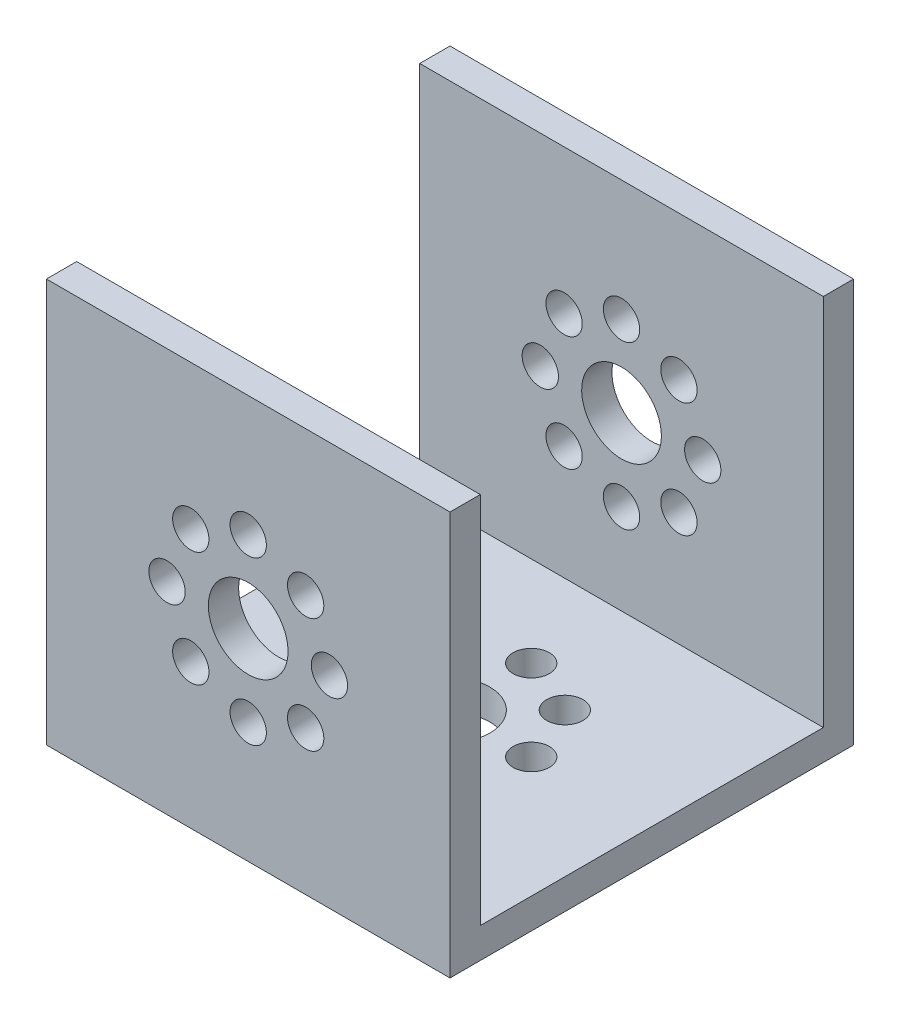
SolidWorks part; units mm, degrees
ref_plane "前视基准面" through (0, 0, 0) normal (0, 0, 1) x (1, 0, 0)
ref_plane "上视基准面" through (0, 0, 0) normal (0, 1, 0) x (1, 0, 0)
ref_plane "右视基准面" through (0, 0, 0) normal (1, 0, 0) x (0, 0, -1)
sketch "c型梁" plane through (0, 0, 0) normal (1, 0, 0) x (0, 0, -1)
  line L0 (-40.2199, 0) -> (42.5339, 0) construction
  line L1 (0, 33.619) -> (0, -33.708) construction
  line L2 (-20, 0) -> (20, 0)
  line L3 (20, 0) -> (20, 40)
  line L4 (20, 40) -> (17, 40)
  line L5 (17, 40) -> (17, 3)
  line L6 (17, 3) -> (-17, 3)
  line L7 (-17, 40) -> (-17, 3)
  line L8 (-20, 40) -> (-17, 40)
  line L9 (-20, 0) -> (-20, 40)
  point P12 (0, 3)
  point P15 (0, 0)
  dimension "D1" = 3
  dimension "D2" = 3
  dimension "D3" = 20
  dimension "D4" = 40
extrude "C型梁1u" add sketch "c型梁" along normal mid plane 40
sketch "8位安装孔" plane through (0, 3, 0) normal (0, 1, 0) x (1, 0, 0)
  line L0 (-25.2434, 0) -> (27.7374, 0) construction
  line L1 (0, 14.9332) -> (0, -14.5682) construction
  circle A0 centre (0, 0) radius 3.95
  circle A1 centre (8.05, 0) radius 1.8
  circle A2 centre (5.6922, -5.6922) radius 1.8
  circle A3 centre (0, -8.05) radius 1.8
  circle A4 centre (-5.6922, -5.6922) radius 1.8
  circle A5 centre (-8.05, 0) radius 1.8
  circle A6 centre (-5.6922, 5.6922) radius 1.8
  circle A7 centre (0, 8.05) radius 1.8
  circle A8 centre (5.6922, 5.6922) radius 1.8
  point P25 (0, 0)
  dimension "D1" = 7.9
  dimension "D2" = 3.6
  dimension "D3" = 8.05
  dimension "D4" = 8
extrude "安装孔" cut sketch "8位安装孔" against normal mid plane 10
pattern_circular "安装孔A侧" count 2 over 360 about axis through (20, 3, 17) along (-1, 0, 0) of "安装孔"
pattern_circular "安装孔B侧" count 2 every 90 about axis through (20, 3, -17) along (-1, 0, 0) of "安装孔"
